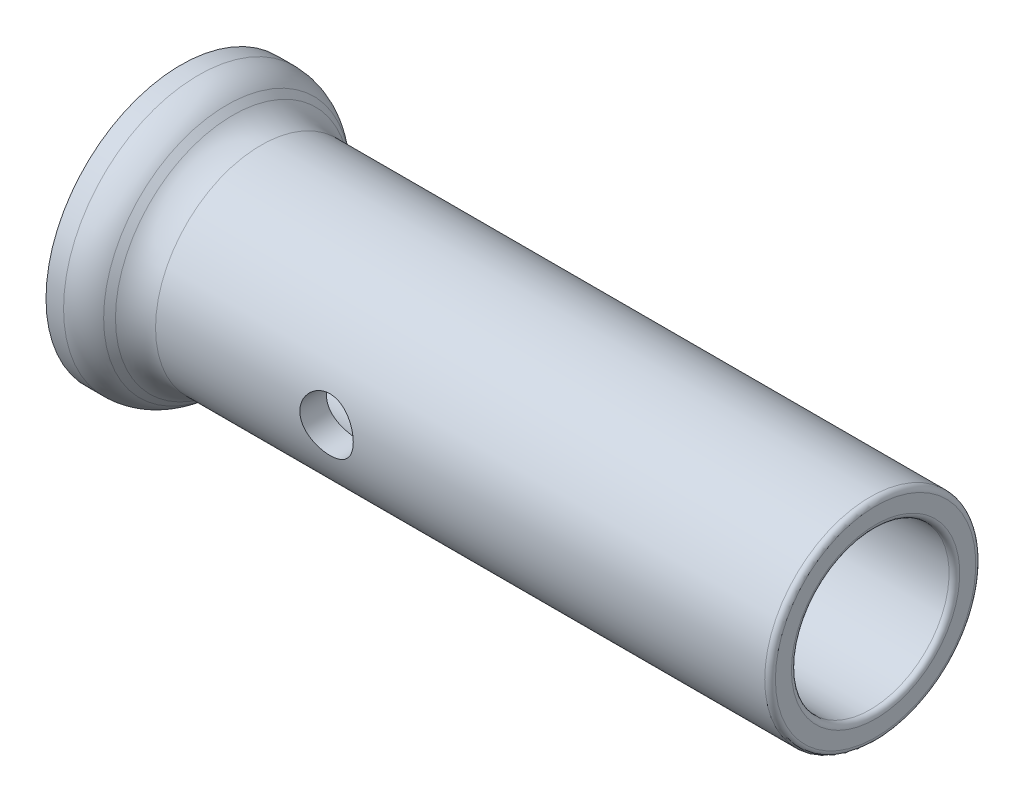
SolidWorks part; units mm, degrees
ref_plane "Plan de face" through (0, 0, 0) normal (0, 0, 1) x (1, 0, 0)
ref_plane "Plan de dessus" through (0, 0, 0) normal (0, 1, 0) x (1, 0, 0)
ref_plane "Plan de droite" through (0, 0, 0) normal (1, 0, 0) x (0, 0, -1)
sketch "Esquisse1" plane through (0, 0, 0) normal (0, 0, 1) x (1, 0, 0)
  line L0 (-11.3006, 0) -> (9.5407, 0) construction
  line L1 (0, 4.05) -> (0, 5.05)
  line L2 (0, 5.05) -> (0.6574, 5.05)
  line L4 (3, 3.95) -> (25.8, 3.95)
  line L5 (26, 3.75) -> (26, 3.15)
  line L6 (25.8, 2.95) -> (1, 2.95)
  line L7 (1, 2.95) -> (1, 4.05)
  line L8 (1, 4.05) -> (0, 4.05)
  line L9 (1.718, 4.6107) -> (1.9393, 4.3893)
  arc A0 (1.9393, 4.3893) -> (3, 3.95) centre (3, 5.45) ccw
  arc A1 (0.6574, 5.05) -> (1.718, 4.6107) centre (0.6574, 3.55) cw
  arc A2 (25.8, 3.95) -> (26, 3.75) centre (25.8, 3.75) cw
  arc A3 (25.8, 2.95) -> (26, 3.15) centre (25.8, 3.15) ccw
  point P13 (2.3787, 3.95)
  point P16 (1.2787, 5.05)
  point P19 (26, 3.95)
  point P22 (26, 2.95)
  dimension "D9" = 1.5
  dimension "D10" = 0.2
  dimension "D11" = 0.2
  dimension "D1" = 8.1
  dimension "D2" = 7.9
  dimension "D3" = 1
  dimension "D4" = 1
  dimension "D5" = 1
  dimension "D6" = 2
  dimension "D7" = 45
  dimension "D8" = 23
revolve "Révolution1" add sketch "Esquisse1" angle 360 about L0
hole_wizard "Dégagement M21" positions "Esquisse3" profile "Esquisse4" hole size "M2" standard "ISO"
sketch "Esquisse3" plane through (0, 0, 0) normal (0, 0, 1) x (1, 0, 0)
  point P0 (9.4, 0)
  dimension "D1" = 9.4
sketch "Esquisse4" plane through (9.4, 0, 0) normal (1, 0, 0) x (0, 1, 0)
  line L0 (0, 0) -> (0, 5.05)
  line L1 (0, 5.05) -> (1, 5.05)
  line L2 (1, 5.05) -> (1, 0)
  line L5 (1, 0) -> (0, 0)
  line L11 (0, -6.35) -> (0, 107.95) construction
  dimension "Diamètre du perçage jusqu'au prochain" = 2
  dimension "Profondeur du perçage jusqu'au prochain" = 5.05
